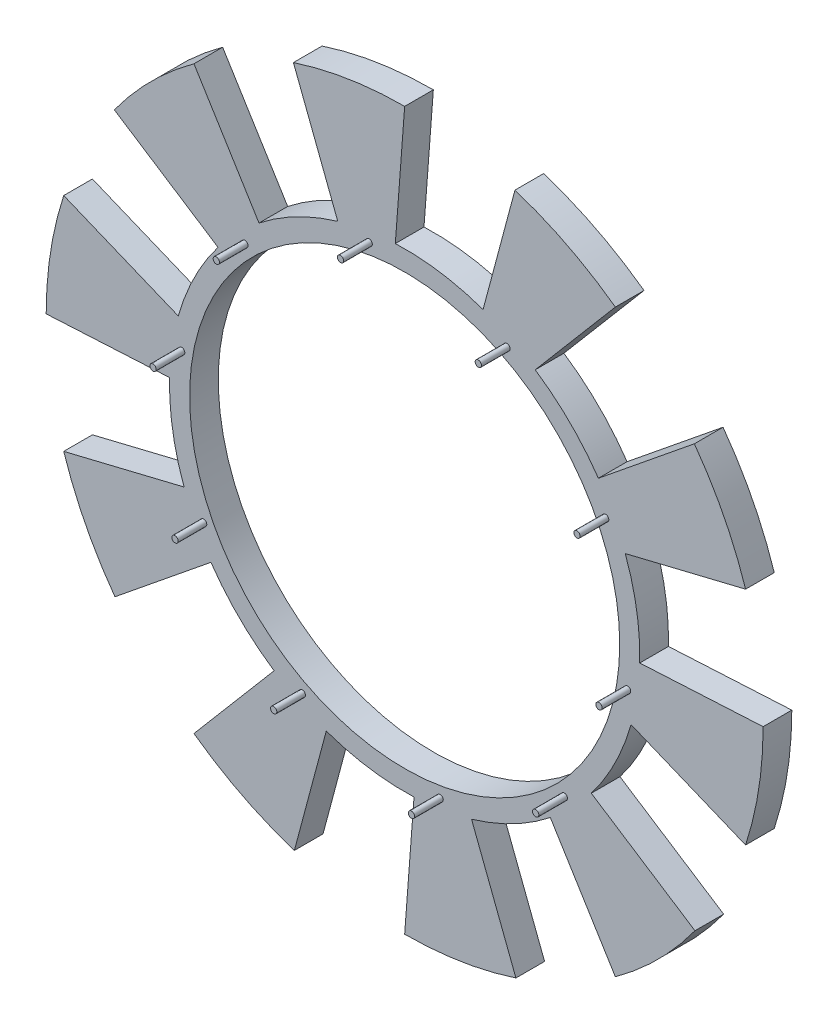
SolidWorks part; units mm, degrees
ref_plane "Front Plane" through (0, 0, 0) normal (0, 0, 1) x (1, 0, 0)
ref_plane "Top Plane" through (0, 0, 0) normal (0, 1, 0) x (1, 0, 0)
ref_plane "Right Plane" through (0, 0, 0) normal (1, 0, 0) x (0, 0, -1)
sketch "Sketch1" plane through (0, 0, 0) normal (0, 0, 1) x (1, 0, 0)
  line L0 (0, 16.4) -> (0, -16.4) construction
  circle A0 centre (0, 0) radius 16.4
  dimension "D1" = 32.8
extrude "Boss-Extrude7" add sketch "Sketch1" along normal blind 2
sketch "Sketch7" plane through (0, 0, 0) normal (0, 0, -1) x (-1, 0, 0)
  line L0 (0, 16.4) -> (0, -16.4) construction
  line L1 (0, -16.4) -> (0, 25) construction
  line L2 (7.7586, 23.7656) -> (4.6647, 15.7226)
  line L3 (0, 25) -> (0.6518, 16.387)
  circle A0 centre (0, 0) radius 16.4 construction
  arc A1 (0, 25) -> (7.7586, 23.7656) centre (0, 0) cw
  arc A2 (0.6518, 16.387) -> (4.6647, 15.7226) centre (0, 0) cw
  dimension "D1" = 25
extrude "Boss-Extrude9" add sketch "Sketch7" against normal blind 2
pattern_circular "CirPattern3" count 10 over 360 about axis through (0, 0, 0) along (0, 0, 1) of "Boss-Extrude7", "Boss-Extrude9"
sketch "Sketch8" plane through (0, 0, 2) normal (0, 0, 1) x (1, 0, 0)
  circle A0 centre (0, 0) radius 15
  dimension "D1" = 30
extrude "Cut-Extrude6" cut sketch "Sketch8" against normal blind 2
sketch "Sketch9" plane through (0, 0, 2) normal (0, 0, 1) x (1, 0, 0)
  line L0 (-3.9281, 24.6895) -> (0, 0)
  arc A0 (0, 25) -> (-7.7586, 23.7656) centre (0, 0) ccw construction
  circle A1 centre (-2.4731, 15.5443) radius 0.219
  point P6 (-2.5755, 16.1876)
  point P7 (-2.5436, 15.9876)
  dimension "D2" = 0.438
  dimension "D1" = 0.2
extrude "Boss-Extrude10" add sketch "Sketch9" along normal blind 2 contours A1
pattern_circular "CirPattern4" count 10 over 360 about axis through (0, 0, 0) along (0, 0, 1) of "Boss-Extrude10"
